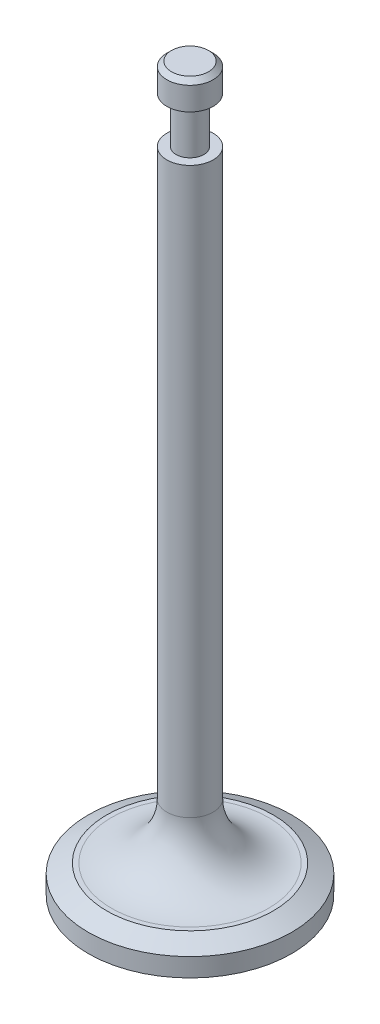
SolidWorks part; units mm, degrees
ref_plane "Front Plane" through (0, 0, 0) normal (0, 0, 1) x (1, 0, 0)
ref_plane "Top Plane" through (0, 0, 0) normal (0, 1, 0) x (1, 0, 0)
ref_plane "Right Plane" through (0, 0, 0) normal (1, 0, 0) x (0, 0, -1)
sketch "Sketch1" plane through (0, 0, 0) normal (1, 0, 0) x (0, 0, -1)
  line L0 (0, 0) -> (0, -78.0671)
  line L1 (0, -78.0671) -> (11, -78.0671)
  line L2 (11, -78.0671) -> (11, -75.0671)
  line L3 (11, -75.0671) -> (2.5, -75.0671)
  line L4 (2.5, -75.0671) -> (2.5, -8)
  line L5 (2.5, -8) -> (1.5, -8)
  line L6 (1.5, -8) -> (1.5, -3)
  line L7 (1.5, -3) -> (2.5, -3)
  line L8 (2.5, -3) -> (2.5, 0)
  line L9 (2.5, 0) -> (0, 0)
  dimension "D1" = 78.0671
  dimension "D2" = 11
  dimension "D3" = 3
  dimension "D4" = 2.5
  dimension "D5" = 3
  dimension "D6" = 5
  dimension "D7" = 1
  dimension "D8" = 2.5
revolve "Revolve1" add sketch "Sketch1" angle 360 about L0
fillet "Fillet1" radius 6 1 edges at (0, -75.0671, 2.5)
chamfer "Chamfer1" distance 1 distance2 2 1 edges at (0, -75.0671, 11)
chamfer "Chamfer2" distance 0.5 angle 45 1 edges at (0, 0, 2.5)
